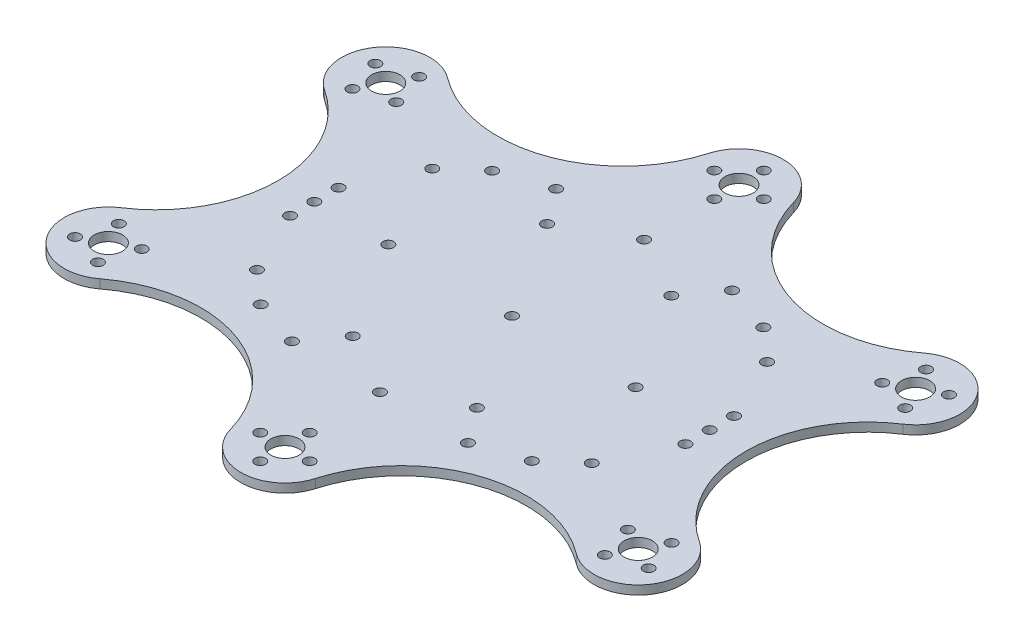
SolidWorks part; units mm, degrees
ref_plane "Front Plane" through (0, 0, 0) normal (0, 0, 1) x (1, 0, 0)
ref_plane "Top Plane" through (0, 0, 0) normal (0, 1, 0) x (1, 0, 0)
ref_plane "Right Plane" through (0, 0, 0) normal (1, 0, 0) x (0, 0, -1)
sketch "Sketch1" plane through (0, 0, 0) normal (0, 1, 0) x (1, 0, 0)
  line L0 (0, 79.6556) -> (0, -85.1852) construction
  line L7 (-100.6518, 0) -> (100.6518, 0) construction
  line L8 (0, 0) -> (74.9766, 39.25) construction
  line L31 (-74.9766, -39.25) -> (74.9766, 39.25) construction
  line L38 (66.25, 79.6556) -> (66.25, -85.1852) construction
  line L39 (-66.25, 79.6556) -> (-66.25, -85.1852) construction
  line L40 (-100.6518, 42) -> (100.6518, 42) construction
  line L41 (-100.6518, -42) -> (100.6518, -42) construction
  line L49 (-74.9766, 39.25) -> (74.9766, -39.25) construction
  line L50 (0, 0) -> (-46.0262, -77.3558) construction
  circle A0 centre (0, 64.25) radius 4
  arc A1 (12.0221, 67.6732) -> (-12.0221, 67.6732) centre (0, 64.25) ccw
  circle A2 centre (0, 64.25) radius 7 construction
  circle A3 centre (-7, 64.25) radius 1.5
  circle A4 centre (0, 57.25) radius 1.5
  circle A5 centre (7, 64.25) radius 1.5
  circle A6 centre (0, 71.25) radius 1.5
  circle A7 centre (0, 37.375) radius 1.5
  circle A8 centre (17.575, 27.5) radius 1.5
  circle A9 centre (24.9, 37.375) radius 1.5
  circle A10 centre (38.375, 32.75) radius 1.5
  circle A11 centre (47.375, 24.8006) radius 1.5
  circle A12 centre (74.9766, 39.25) radius 4
  arc A13 (81.8194, 28.7893) -> (67.4147, 49.2033) centre (74.9766, 39.25) ccw
  circle A14 centre (74.9766, 39.25) radius 7 construction
  circle A15 centre (68.775, 36.0035) radius 1.5
  circle A16 centre (71.7301, 45.4516) radius 1.5
  circle A17 centre (81.1782, 42.4965) radius 1.5
  circle A18 centre (78.2231, 33.0484) radius 1.5
  circle A21 centre (35, 0) radius 1.5
  circle A22 centre (-35, 0) radius 1.5
  circle A23 centre (-47.375, 24.8006) radius 1.5
  circle A24 centre (-38.375, 32.75) radius 1.5
  circle A25 centre (-17.575, 27.5) radius 1.5
  circle A28 centre (-24.9, 37.375) radius 1.5
  circle A29 centre (-74.9766, 39.25) radius 7 construction
  circle A30 centre (-78.2231, 33.0484) radius 1.5
  circle A31 centre (-81.1782, 42.4965) radius 1.5
  circle A32 centre (-71.7301, 45.4516) radius 1.5
  circle A33 centre (-68.775, 36.0035) radius 1.5
  arc A34 (-81.8194, 28.7893) -> (-67.4147, 49.2033) centre (-74.9766, 39.25) cw
  circle A35 centre (-74.9766, 39.25) radius 4
  circle A36 centre (-24.9, -37.375) radius 1.5
  circle A37 centre (-17.575, -27.5) radius 1.5
  circle A38 centre (-38.375, -32.75) radius 1.5
  circle A39 centre (-47.375, -24.8006) radius 1.5
  circle A40 centre (47.375, -24.8006) radius 1.5
  circle A41 centre (38.375, -32.75) radius 1.5
  circle A42 centre (24.9, -37.375) radius 1.5
  circle A43 centre (17.575, -27.5) radius 1.5
  circle A44 centre (0, -37.375) radius 1.5
  circle A49 centre (0, -64.25) radius 7 construction
  circle A50 centre (0, -71.25) radius 1.5
  circle A51 centre (7, -64.25) radius 1.5
  circle A52 centre (0, -57.25) radius 1.5
  circle A53 centre (-7, -64.25) radius 1.5
  arc A54 (12.0221, -67.6732) -> (-12.0221, -67.6732) centre (0, -64.25) cw
  circle A55 centre (0, -64.25) radius 4
  circle A56 centre (74.9766, -39.25) radius 7 construction
  circle A57 centre (78.2231, -33.0484) radius 1.5
  circle A58 centre (81.1782, -42.4965) radius 1.5
  circle A59 centre (71.7301, -45.4516) radius 1.5
  circle A60 centre (68.775, -36.0035) radius 1.5
  arc A61 (81.8194, -28.7893) -> (67.4147, -49.2033) centre (74.9766, -39.25) cw
  circle A62 centre (74.9766, -39.25) radius 4
  circle A63 centre (-74.9766, -39.25) radius 7 construction
  circle A64 centre (-74.9766, -39.25) radius 4
  arc A65 (-81.8194, -28.7893) -> (-67.4147, -49.2033) centre (-74.9766, -39.25) ccw
  circle A66 centre (-68.775, -36.0035) radius 1.5
  circle A67 centre (-71.7301, -45.4516) radius 1.5
  circle A68 centre (-81.1782, -42.4965) radius 1.5
  circle A69 centre (-78.2231, -33.0484) radius 1.5
  arc A70 (-81.8194, -28.7893) -> (-81.8194, 28.7893) centre (-100.6518, 0) ccw
  arc A71 (81.8194, -28.7893) -> (81.8194, 28.7893) centre (100.6518, 0) cw
  arc A72 (-12.0221, -67.6732) -> (-67.4147, -49.2033) centre (-46.0262, -77.3558) ccw
  arc A73 (-12.0221, 67.6732) -> (-67.4147, 49.2033) centre (-46.0262, 77.3558) cw
  arc A74 (12.0221, -67.6732) -> (67.4147, -49.2033) centre (46.0262, -77.3558) cw
  arc A75 (12.0221, 67.6732) -> (67.4147, 49.2033) centre (46.0262, 77.3558) ccw
  circle A78 centre (-44.9, 0) radius 4 construction
  circle A79 centre (-55.95, 0) radius 1.5
  circle A80 centre (-55.95, 6.875) radius 1.5
  circle A81 centre (-55.95, -6.875) radius 1.5
  circle A82 centre (55.95, 6.875) radius 1.5
  circle A83 centre (55.95, 0) radius 1.5
  circle A84 centre (55.95, -6.875) radius 1.5
  circle A85 centre (0, 0) radius 1.5
  point P0 (0, 0)
  point P25 (0, 64.25)
  point P49 (74.9766, 39.25)
  point P89 (52.4508, 0)
  point P91 (-74.9766, 39.25)
  point P145 (0, -64.25)
  point P158 (74.9766, -39.25)
  point P171 (-74.9766, -39.25)
  dimension "D3" = 25
  dimension "D4" = 8
  dimension "D5" = 14
  dimension "D6" = 3
  dimension "D13" = 74.75
  dimension "D14" = 24.9
  dimension "D15" = 137.55
  dimension "D17" = 35.15
  dimension "D18" = 70
  dimension "D19" = 94.75
  dimension "D20" = 78.5
  dimension "D21" = 76.75
  dimension "D22" = 65.5
  dimension "D23" = 128.5
  dimension "D24" = 132.5
  dimension "D25" = 84
  dimension "D26" = 55
  dimension "D31" = 13.75
  dimension "D32" = 11.05
  dimension "D33" = 9.9
  dimension "D7" = 4
  dimension "D8" = 4
extrude "Boss-Extrude1" add sketch "Sketch1" along normal blind 2.5
